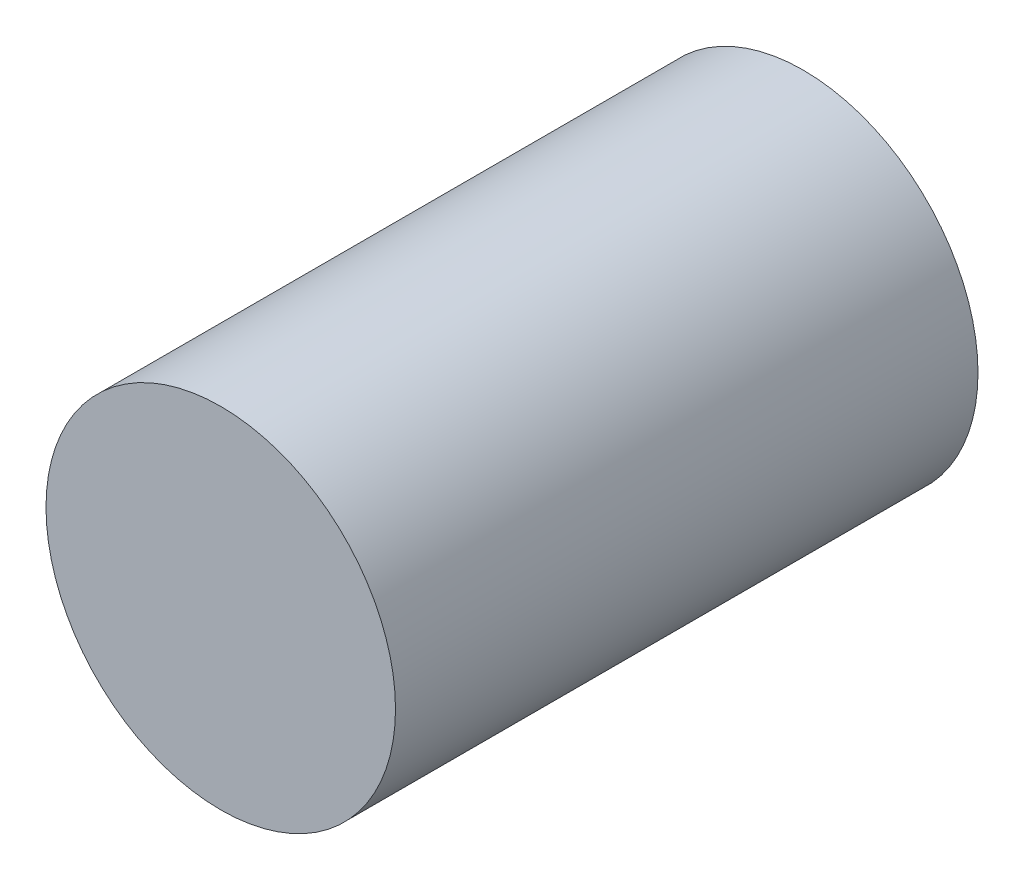
SolidWorks part; units mm, degrees
ref_plane "Front Plane" through (0, 0, 0) normal (0, 0, 1) x (1, 0, 0)
ref_plane "Top Plane" through (0, 0, 0) normal (0, 1, 0) x (1, 0, 0)
ref_plane "Right Plane" through (0, 0, 0) normal (1, 0, 0) x (0, 0, -1)
sketch "Sketch1" plane through (0, 0, 0) normal (0, 0, 1) x (1, 0, 0)
  circle A0 centre (0, 0) radius 30
  dimension "D1" = 60
extrude "Boss-Extrude1" add sketch "Sketch1" along normal blind 100
sketch "Sketch2" plane through (0, 0, 0) normal (0, 1, 0) x (1, 0, 0)
  line L0 (0, 0) -> (30, 0)
  line L1 (0, 3.0306) -> (0, 0)
  arc A0 (0, 3.0306) -> (30, 0) centre (0, -146.9694) cw
revolve "Revolve1" add sketch "Sketch2" angle 360 about L1
